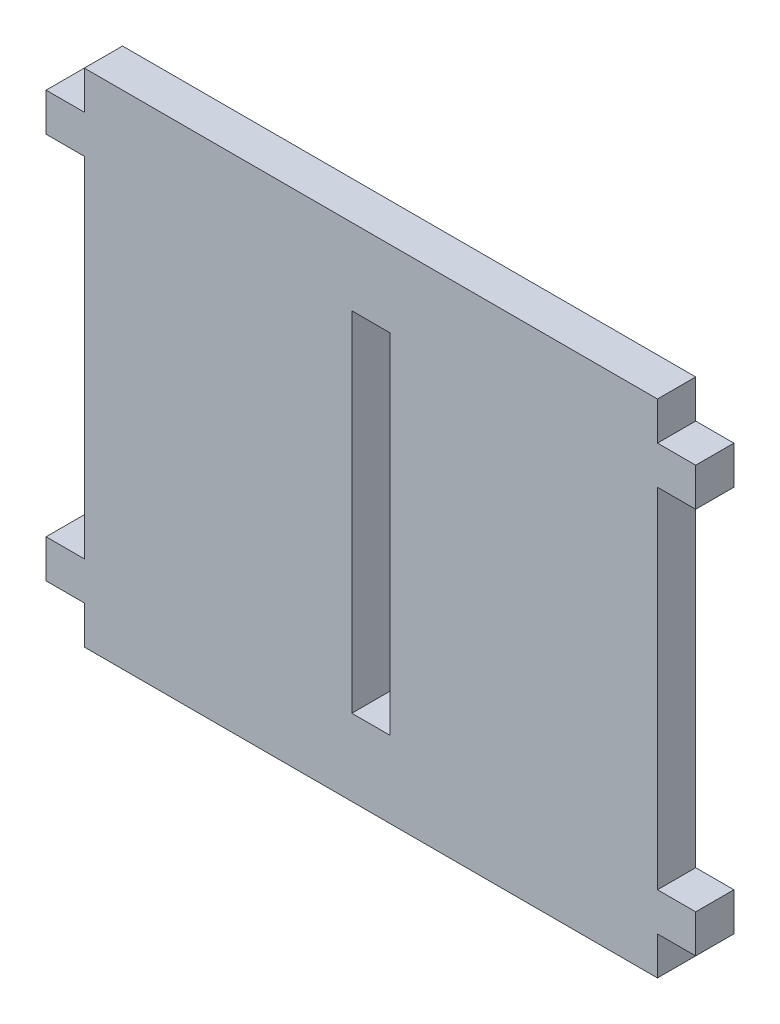
SolidWorks part; units mm, degrees
ref_plane "Front Plane" through (0, 0, 0) normal (0, 0, 1) x (1, 0, 0)
ref_plane "Top Plane" through (0, 0, 0) normal (0, 1, 0) x (1, 0, 0)
ref_plane "Right Plane" through (0, 0, 0) normal (1, 0, 0) x (0, 0, -1)
sketch "Sketch1" plane through (0, 0, 0) normal (0, 0, 1) x (1, 0, 0)
  line L0 (-101.6, 35.3139) -> (-107.95, 35.3139)
  line L1 (0, 35.3139) -> (-6.35, 35.3139)
  line L2 (0, 35.3139) -> (0, 28.9639)
  line L3 (0, -35.3139) -> (-6.35, -35.3139)
  line L4 (-107.95, 35.3139) -> (-107.95, 28.9639)
  line L5 (-101.6, -35.3139) -> (-107.95, -35.3139)
  line L6 (-6.35, 35.3139) -> (-6.35, 41.6639)
  line L7 (-6.35, 41.6639) -> (-101.6, 41.6639)
  line L8 (-101.6, 35.3139) -> (-101.6, 41.6639)
  line L9 (0, -28.9639) -> (0, -35.3139)
  line L10 (-6.35, -35.3139) -> (-6.35, -41.6639)
  line L11 (-6.35, -41.6639) -> (-101.6, -41.6639)
  line L12 (-101.6, -35.3139) -> (-101.6, -41.6639)
  line L13 (-107.95, -28.9639) -> (-107.95, -35.3139)
  line L16 (-50.8, -28.9639) -> (-50.8, 28.9639)
  line L17 (-57.15, -28.9639) -> (-50.8, -28.9639)
  line L18 (-57.15, 28.9639) -> (-57.15, -28.9639)
  line L19 (-50.8, 28.9639) -> (-57.15, 28.9639)
  line L20 (-50.8, -28.9639) -> (-50.8, 28.9639)
  line L21 (-57.15, -28.9639) -> (-50.8, -28.9639)
  line L22 (-57.15, 28.9639) -> (-57.15, -28.9639)
  line L23 (-50.8, 28.9639) -> (-57.15, 28.9639)
  line L24 (0, -28.9639) -> (0, 28.9639)
  line L25 (-6.35, -28.9639) -> (0, -28.9639)
  line L26 (-6.35, 28.9639) -> (-6.35, -28.9639)
  line L27 (0, 28.9639) -> (-6.35, 28.9639)
  line L29 (-6.35, -28.9639) -> (0, -28.9639)
  line L30 (-6.35, 28.9639) -> (-6.35, -28.9639)
  line L31 (0, 28.9639) -> (-6.35, 28.9639)
  line L32 (-101.6, -28.9639) -> (-101.6, 28.9639)
  line L33 (-107.95, -28.9639) -> (-101.6, -28.9639)
  line L34 (-107.95, 28.9639) -> (-107.95, -28.9639)
  line L35 (-101.6, 28.9639) -> (-107.95, 28.9639)
  line L36 (-101.6, -28.9639) -> (-101.6, 28.9639)
  line L37 (-107.95, -28.9639) -> (-101.6, -28.9639)
  line L39 (-101.6, 28.9639) -> (-107.95, 28.9639)
  dimension "D1" = 0
  dimension "D2" = 0
  dimension "D3" = 0
extrude "Boss-Extrude1" add sketch "Sketch1" along normal blind 6.35
